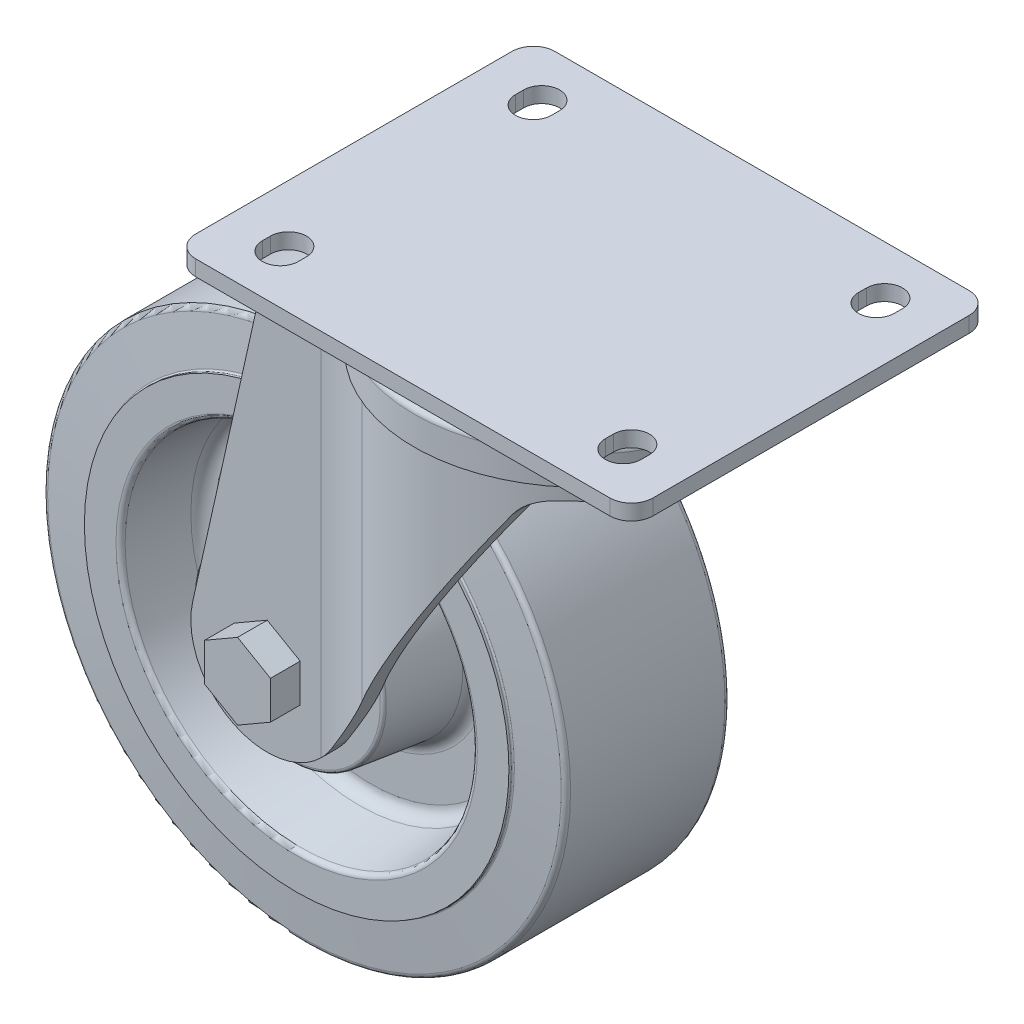
SolidWorks part; units mm, degrees
ref_plane "Front Plane" through (0, 0, 0) normal (0, 0, 1) x (1, 0, 0)
ref_plane "Top Plane" through (0, 0, 0) normal (0, 1, 0) x (1, 0, 0)
ref_plane "Right Plane" through (0, 0, 0) normal (1, 0, 0) x (0, 0, -1)
ref_plane "Plane4" through (0, 95.036, 0) normal (0, 1, 0) x (1, 0, 0)
sketch "Sketch1" plane through (0, 95.036, 0) normal (0, 1, 0) x (1, 0, 0)
  line L0 (-28.205, 36.5) -> (-28.205, -36.5)
  line L1 (-28.205, -36.5) -> (16.4828, -36.5)
  line L2 (16.4828, 36.5) -> (-28.205, 36.5)
  arc A0 (16.4828, -36.5) -> (33.9958, -41.5305) centre (16.4828, -69.5) cw
  arc A1 (33.9958, -41.5305) -> (33.9958, 41.5305) centre (60, 0) ccw
  arc A2 (33.9958, 41.5305) -> (16.4828, 36.5) centre (16.4828, 69.5) cw
extrude "Boss-Extrude1" add sketch "Sketch1" against normal blind 119.805
sketch "Sketch2" plane through (0, 0, 0) normal (0, 0, 1) x (1, 0, 0)
  line L0 (-55, -65) -> (160, -65)
  line L1 (160, -65) -> (160, 130)
  line L2 (160, 130) -> (-55, 130)
  line L3 (-55, 130) -> (-55, -65)
  line L4 (19.6667, -12.6799) -> (82.3201, 84.4966)
  line L5 (91.5652, 89.536) -> (100.76, 89.536)
  line L6 (100.76, 89.536) -> (100.76, 96.036)
  line L7 (100.76, 96.036) -> (-2.53, 96.036)
  line L8 (-2.53, 96.036) -> (-22.8375, 5.1)
  arc A0 (-22.8375, 5.1) -> (19.6667, -12.6799) centre (0, 0) ccw
  arc A1 (82.3201, 84.4966) -> (91.5652, 89.536) centre (91.5652, 78.536) cw
extrude "Cut-Extrude1" cut sketch "Sketch2" along normal blind 110 and the other way blind 110
ref_plane "Plane5" through (0, 89.536, 0) normal (0, 1, 0) x (1, 0, 0)
sketch "Sketch3" plane through (0, 89.536, 0) normal (0, 1, 0) x (1, 0, 0)
  line L0 (-28.205, 31.5) -> (-28.205, -31.5)
  line L1 (-28.205, -31.5) -> (17.9435, -31.5)
  line L2 (17.9435, 31.5) -> (-28.205, 31.5)
  arc A0 (17.9435, -31.5) -> (35.9677, -36.8571) centre (17.9435, -64.5) cw
  arc A1 (35.9677, -36.8571) -> (35.9677, 36.8571) centre (60, 0) ccw
  arc A2 (35.9677, 36.8571) -> (17.9435, 31.5) centre (17.9435, 64.5) cw
sketch "Sketch4" plane through (0, 0, 0) normal (0, 0, 1) x (1, 0, 0)
  line L0 (60, 95.026) -> (8.48, 95.026)
  line L1 (8.48, 95.026) -> (8.48, 103.751)
  line L2 (10.68, 105.951) -> (11.56, 105.951)
  line L3 (8.48, 109.031) -> (8.48, 110.7235)
  line L4 (8.48, 110.7235) -> (60, 110.7235)
  line L5 (60, 110.7235) -> (60, 95.026)
  line L6 (60, 110.7235) -> (60, 95.026) construction
  arc A0 (8.48, 103.751) -> (10.68, 105.951) centre (10.68, 103.751) cw
  arc A1 (11.56, 105.951) -> (8.48, 109.031) centre (11.56, 109.031) cw
revolve "Revolve1" add sketch "Sketch4" angle 360 about L6
ref_plane "Plane6" through (0, 115, 0) normal (0, 1, 0) x (1, 0, 0)
extrude "Cut-Extrude2" cut sketch "Sketch3" against normal blind 195
sketch "Sketch5" plane through (0, 115, 0) normal (0, 1, 0) x (1, 0, 0)
  line L0 (-10, 48.4) -> (-10, -48.4)
  line L1 (-3.4, -55) -> (123.4, -55)
  line L2 (130, -48.4) -> (130, 48.4)
  line L3 (123.4, 55) -> (-3.4, 55)
  line L4 (118, 37.5) -> (118, 40)
  line L5 (107, 40) -> (107, 37.5)
  line L6 (107, -37.5) -> (107, -40)
  line L7 (118, -40) -> (118, -37.5)
  line L8 (13, 37.5) -> (13, 40)
  line L9 (2, 40) -> (2, 37.5)
  line L10 (2, -37.5) -> (2, -40)
  line L11 (13, -40) -> (13, -37.5)
  arc A0 (-10, -48.4) -> (-3.4, -55) centre (-3.4, -48.4) ccw
  arc A1 (123.4, -55) -> (130, -48.4) centre (123.4, -48.4) ccw
  arc A2 (130, 48.4) -> (123.4, 55) centre (123.4, 48.4) ccw
  arc A3 (-3.4, 55) -> (-10, 48.4) centre (-3.4, 48.4) ccw
  arc A4 (107, 37.5) -> (118, 37.5) centre (112.5, 37.5) ccw
  arc A5 (118, 40) -> (107, 40) centre (112.5, 40) ccw
  arc A6 (107, -40) -> (118, -40) centre (112.5, -40) ccw
  arc A7 (118, -37.5) -> (107, -37.5) centre (112.5, -37.5) ccw
  arc A8 (2, 37.5) -> (13, 37.5) centre (7.5, 37.5) ccw
  arc A9 (13, 40) -> (2, 40) centre (7.5, 40) ccw
  arc A10 (2, -40) -> (13, -40) centre (7.5, -40) ccw
  arc A11 (13, -37.5) -> (2, -37.5) centre (7.5, -37.5) ccw
extrude "Boss-Extrude2" add sketch "Sketch5" against normal blind 4.7725
sketch "Sketch6" plane through (0, 0, 0) normal (1, 0, 0) x (0, 0, -1)
  line L0 (-31.525, 0) -> (-31.525, 10.01)
  line L1 (-31.525, 10.01) -> (31.525, 10.01)
  line L2 (31.525, 10.01) -> (31.525, 0)
  line L3 (31.525, 0) -> (-31.525, 0)
  line L4 (31.525, 0) -> (-31.525, 0) construction
revolve "Revolve2" add sketch "Sketch6" angle 360 about L4
ref_plane "Plane7" through (0, 0, 45.6) normal (0, 0, 1) x (1, 0, 0)
sketch "Sketch7" plane through (0, 0, 45.6) normal (0, 0, 1) x (1, 0, 0)
  line L0 (-10.08, -5.8197) -> (0, -11.6394)
  line L1 (0, -11.6394) -> (10.08, -5.8197)
  line L2 (10.08, -5.8197) -> (10.08, 5.8197)
  line L3 (10.08, 5.8197) -> (0, 11.6394)
  line L4 (0, 11.6394) -> (-10.08, 5.8197)
  line L5 (-10.08, 5.8197) -> (-10.08, -5.8197)
extrude "Boss-Extrude3" add sketch "Sketch7" against normal blind 9.2
ref_plane "Plane8" through (0, 0, -45.6) normal (0, 0, 1) x (1, 0, 0)
sketch "Sketch8" plane through (0, 0, -45.6) normal (0, 0, 1) x (1, 0, 0)
  line L0 (-10.08, -5.8197) -> (0, -11.6394)
  line L1 (0, -11.6394) -> (10.08, -5.8197)
  line L2 (10.08, -5.8197) -> (10.08, 5.8197)
  line L3 (10.08, 5.8197) -> (0, 11.6394)
  line L4 (0, 11.6394) -> (-10.08, 5.8197)
  line L5 (-10.08, 5.8197) -> (-10.08, -5.8197)
extrude "Boss-Extrude4" add sketch "Sketch8" along normal blind 9.2
sketch "Sketch9" plane through (0, 0, 0) normal (1, 0, 0) x (0, 0, -1)
  line L0 (-30, 28.1153) -> (-30, 10)
  line L1 (-30, 10) -> (30, 10)
  line L2 (30, 10) -> (30, 28.1153)
  line L3 (29.1219, 29.1078) -> (8.2625, 31.669)
  line L4 (4.75, 35.6392) -> (4.75, 47.6678)
  line L5 (8.2625, 51.6379) -> (26.1828, 53.8383)
  line L6 (27.5, 55.3271) -> (27.5, 65)
  line L7 (27.5, 65) -> (26.7705, 65)
  line L8 (26.2724, 65.4564) -> (25.1198, 78.6307)
  line L9 (23.6255, 80) -> (-23.6255, 80)
  line L10 (-25.1198, 78.6307) -> (-26.2724, 65.4564)
  line L11 (-26.7705, 65) -> (-27.5, 65)
  line L12 (-27.5, 65) -> (-27.5, 55.3271)
  line L13 (-26.1828, 53.8383) -> (-8.2625, 51.6379)
  line L14 (-4.75, 47.6678) -> (-4.75, 35.6392)
  line L15 (-8.2625, 31.669) -> (-29.1219, 29.1078)
  line L16 (30, 0) -> (-30, 0) construction
  arc A0 (30, 28.1153) -> (29.1219, 29.1078) centre (29, 28.1153) ccw
  arc A1 (8.2625, 31.669) -> (4.75, 35.6392) centre (8.75, 35.6392) cw
  arc A2 (4.75, 47.6678) -> (8.2625, 51.6379) centre (8.75, 47.6678) cw
  arc A3 (26.1828, 53.8383) -> (27.5, 55.3271) centre (26, 55.3271) ccw
  arc A4 (26.7705, 65) -> (26.2724, 65.4564) centre (26.7705, 65.5) cw
  arc A5 (25.1198, 78.6307) -> (23.6255, 80) centre (23.6255, 78.5) ccw
  arc A6 (-23.6255, 80) -> (-25.1198, 78.6307) centre (-23.6255, 78.5) ccw
  arc A7 (-26.2724, 65.4564) -> (-26.7705, 65) centre (-26.7705, 65.5) cw
  arc A8 (-27.5, 55.3271) -> (-26.1828, 53.8383) centre (-26, 55.3271) ccw
  arc A9 (-8.2625, 51.6379) -> (-4.75, 47.6678) centre (-8.75, 47.6678) cw
  arc A10 (-4.75, 35.6392) -> (-8.2625, 31.669) centre (-8.75, 35.6392) cw
  arc A11 (-29.1219, 29.1078) -> (-30, 28.1153) centre (-29, 28.1153) ccw
revolve "Revolve3" add sketch "Sketch9" angle 360 about L16
ref_plane "Plane9" through (60, 0, 0) normal (1, 0, 0) x (0, 0, -1)
